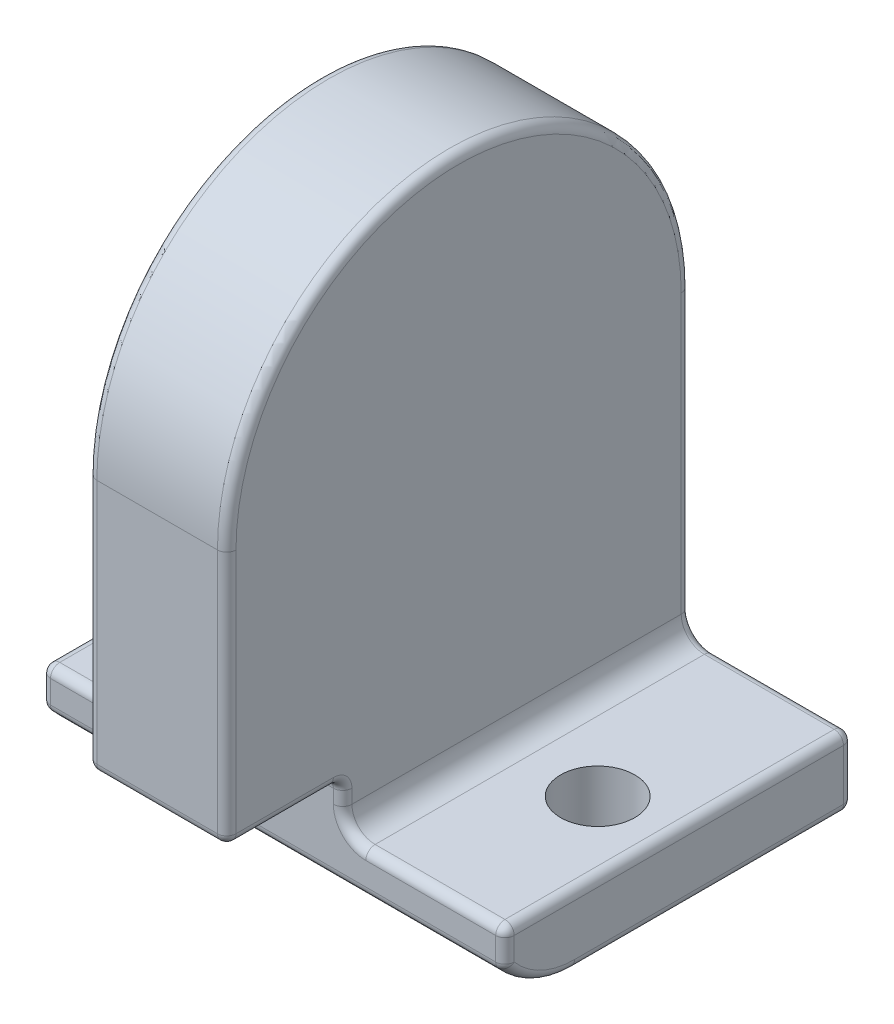
SolidWorks part; units mm, degrees
ref_plane "前视基准面" through (0, 0, 0) normal (0, 0, 1) x (1, 0, 0)
ref_plane "上视基准面" through (0, 0, 0) normal (0, 1, 0) x (1, 0, 0)
ref_plane "右视基准面" through (0, 0, 0) normal (1, 0, 0) x (0, 0, -1)
sketch "草图1" plane through (0, 0, 0) normal (1, 0, 0) x (0, 0, -1)
  line L0 (-5, 0) -> (-5, -8)
  line L1 (5, 0) -> (5, -8)
  line L2 (5, -8) -> (-5, -8)
  circle A0 centre (0, 0) radius 3
  arc A1 (5, 0) -> (-5, 0) centre (0, 0) ccw
extrude "凸台-拉伸1" add sketch "草图1" along normal blind 3
sketch "草图2" plane through (0, -8, 0) normal (0, -1, 0) x (1, 0, 0)
  line L0 (3, 5) -> (3, -5) construction
  line L1 (6.5, -5) -> (-3.5, -5)
  line L3 (6.5, 5) -> (-3.5, 5)
  line L4 (-3.5, -5) -> (-3.5, 5)
  line L6 (0, 5) -> (0, -5) construction
  line L8 (6.5, -5) -> (6.5, 5)
  circle A0 centre (5, -1) radius 0.8
  circle A1 centre (-2, -1) radius 0.8
  dimension "D1" = 3.5
  dimension "D3" = 1.6
  dimension "D5" = 2
  dimension "D6" = 1.6
  dimension "D7" = 4
  dimension "D8" = 4
  dimension "D4" = 2
  dimension "D2" = 3.5
extrude "凸台-拉伸2" add sketch "草图2" against normal blind 1.5
sketch "草图3" plane through (3, 0, 0) normal (1, 0, 0) x (0, 0, -1)
  circle A0 centre (0, 0) radius 3.9779
sketch "草图5" plane through (0, -8, 0) normal (0, -1, 0) x (1, 0, 0)
  line L0 (6.5, -5) -> (6.5, 5) construction
  line L2 (-3.5, 5) -> (6.5, 5)
  line L3 (-3.5, 5) -> (-3.5, 2.5)
  line L5 (-3.5, 2.5) -> (6.5, 2.5)
  line L6 (6.5, 5) -> (6.5, 2.5)
extrude "切除-拉伸1" cut sketch "草图5" against normal blind 2.5
sketch "草图6" plane through (-3.5, 0, 0) normal (-1, 0, 0) x (0, 0, 1)
  line L2 (2.8974, -6) -> (3.2771, -6)
  line L3 (1, -8) -> (1, -8.3251)
  line L4 (1, -8.3251) -> (3.2771, -8.3251)
  line L5 (3.2771, -6) -> (3.2771, -8.3251)
  arc A0 (1, -8) -> (2.8974, -6) centre (1, -6.1) ccw
extrude "切除-拉伸2" cut sketch "草图6" against normal up to next
fillet "圆角1" radius 0.5 2 edges at (0, -6.5, -1.25) (3, -6.5, -1.25)
fillet "圆角2" radius 0.2 32 edges at (5, -6.5, -5) (3.1464, -6.3536, -5) (3, -3, -5) (3, -2.75, 5) (-2, -6.5, -5) (-0.1464, -6.3536, -5) (0, -3, -5) (0, -2.75, 5) (6.5, -8, -2) (6.5, -6.5, -1.25) (-3.5, -6.5, -1.25) (-3.5, -8, -2) (-3.5, -7.25, -5) (6.5, -7.25, -5) (3, 5, 0) (0, 5, 0) (3, -5.5, 3.75) (0, -5.5, 3.75) (1.5, -5.5, 5) (6.5, -7.8067, 1.8349) (-3.5, -7.8067, 1.8349) (1.5, -8, -5) (-2, -6.5, 2.5) (5, -6.5, 2.5) (-0.1464, -6.3536, 2.5) (3.1464, -6.3536, 2.5) (0, -5.75, 2.5) (3, -5.75, 2.5) (1.5, -7.2662, 2.5) (6.5, -6.8831, 2.5) (-3.5, -6.8831, 2.5) (1.5, -5.5, 2.5)
chamfer "倒角1" distance 0.2 angle 45 2 edges at (0, 0, -3) (3, 0, -3)
extrude "凸台-拉伸3" add sketch "草图3" against normal blind 0.4
